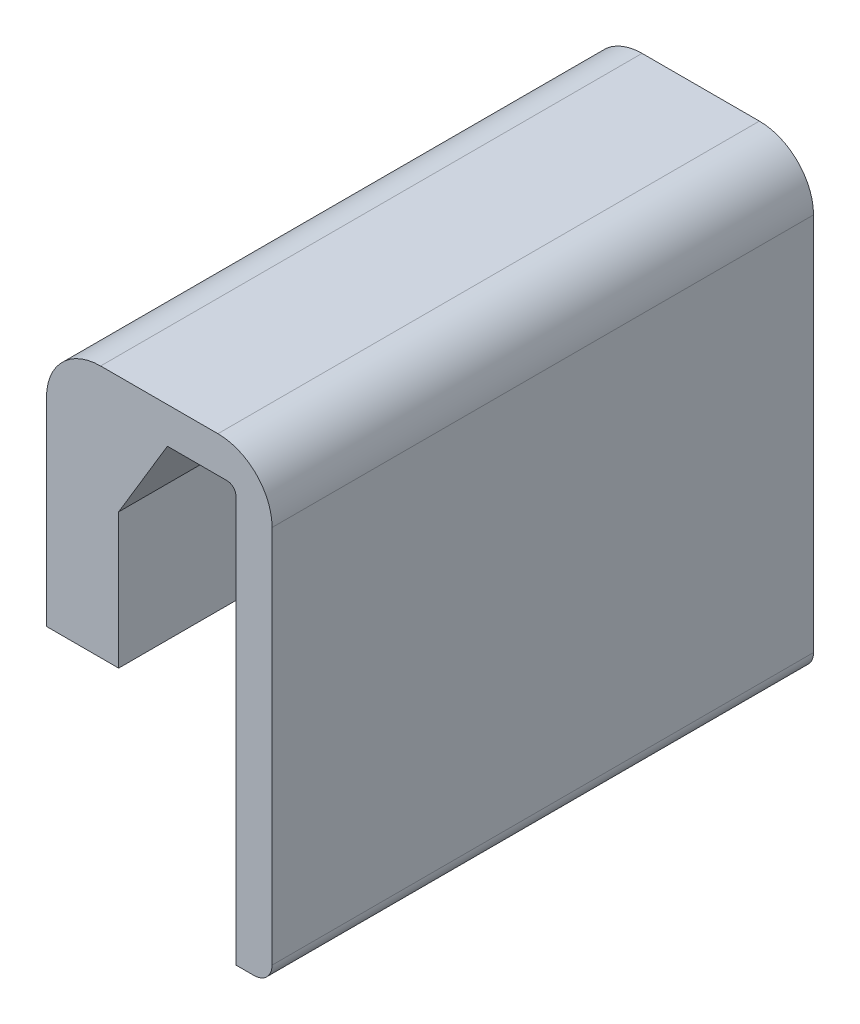
SolidWorks part; units mm, degrees
ref_plane "Front Plane" through (0, 0, 0) normal (0, 0, 1) x (1, 0, 0)
ref_plane "Top Plane" through (0, 0, 0) normal (0, 1, 0) x (1, 0, 0)
ref_plane "Right Plane" through (0, 0, 0) normal (1, 0, 0) x (0, 0, -1)
sketch "Sketch1" plane through (0, 0, 0) normal (0, 0, 1) x (1, 0, 0)
  line L0 (0, 0) -> (0, 50)
  line L1 (0, 50) -> (12.5, 50)
  line L2 (12.5, 50) -> (12.5, 25)
  line L3 (12.5, 25) -> (10.5, 25)
  line L4 (10.5, 25) -> (10.5, 48)
  line L5 (10.5, 48) -> (6.7, 48)
  line L6 (6.7, 48) -> (4, 43.5)
  line L7 (4, 43.5) -> (4, 0)
  line L8 (4, 0) -> (0, 0)
  dimension "D1" = 3.8
  dimension "D2" = 2.7
  dimension "D3" = 2
  dimension "D4" = 2
  dimension "D5" = 4
  dimension "D6" = 4.5
  dimension "D7" = 25
  dimension "D8" = 50
extrude "Boss-Extrude1" add sketch "Sketch1" along normal blind 30
fillet "Fillet1" radius 3 2 edges at (12.5, 50, 15) (0, 50, 15)
fillet "Fillet2" radius 0.5 1 edges at (10.5, 48, 15)
fillet "Fillet3" radius 1 1 edges at (12.5, 25, 15)
sketch "Sketch2" plane through (0, 0, 0) normal (-1, 0, 0) x (0, 0, 1)
  line L0 (10, 42) -> (20, 42)
  line L1 (0, 47) -> (0, 0) construction
  line L2 (30, 47) -> (30, 0) construction
  line L3 (0, 36) -> (12, 36)
  line L4 (18, 36) -> (30, 36)
  line L10 (12, 36) -> (10, 42)
  line L11 (18, 36) -> (20, 42)
  line L12 (0, 36) -> (0, 0)
  line L13 (0, 0) -> (30, 0)
  line L14 (30, 36) -> (30, 0)
  dimension "D1" = 10
  dimension "D2" = 6
  dimension "D3" = 11
  dimension "D4" = 6
  dimension "D5" = 71.565
extrude "Cut-Extrude1" cut sketch "Sketch2" against normal blind 10
